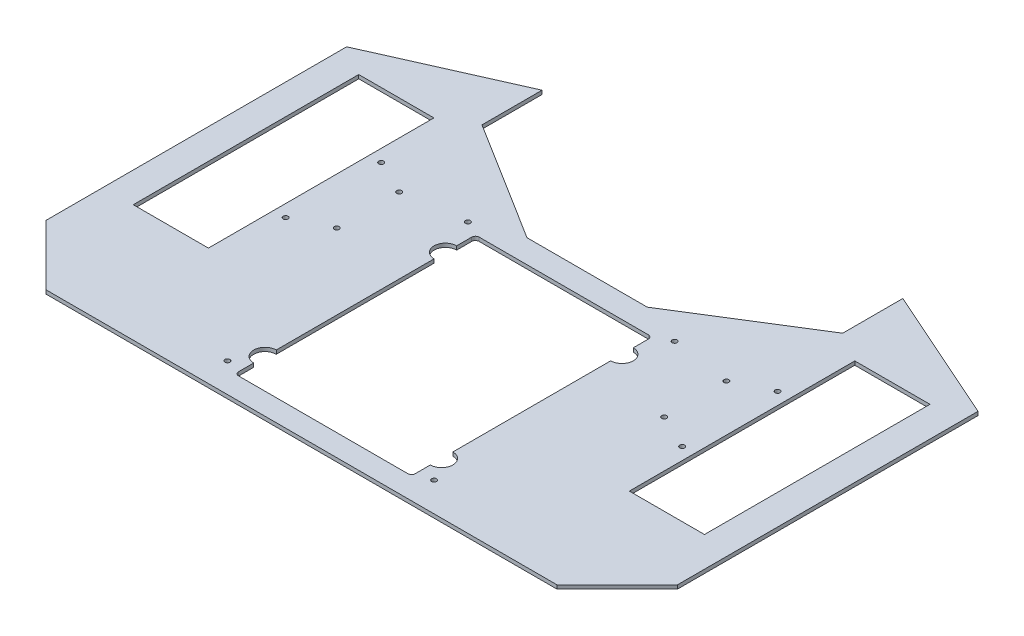
SolidWorks part; units mm, degrees
material "Balsa"
ref_plane "Front Plane" through (0, 0, 0) normal (0, 0, 1) x (1, 0, 0)
ref_plane "Top Plane" through (0, 0, 0) normal (0, 1, 0) x (1, 0, 0)
ref_plane "Right Plane" through (0, 0, 0) normal (1, 0, 0) x (0, 0, -1)
sketch "Sketch1" plane through (0, 0, 0) normal (0, 1, 0) x (1, 0, 0)
  line L17 (265.3132, -148.5502) -> (201.8132, -148.5502) construction
  line L18 (265.3132, -148.5502) -> (265.3132, -339.0502) construction
  line L19 (265.3132, -339.0502) -> (201.8132, -339.0502) construction
  line L20 (201.8132, -148.5502) -> (201.8132, -339.0502) construction
  line L21 (-153.7868, -148.5502) -> (-153.7868, -339.0502) construction
  line L22 (-217.2868, -339.0502) -> (-153.7868, -339.0502) construction
  line L23 (-217.2868, -148.5502) -> (-217.2868, -339.0502) construction
  line L24 (-217.2868, -148.5502) -> (-153.7868, -148.5502) construction
  line L25 (-242.6868, -133.4325) -> (-242.6868, -385.4912) construction
  line L26 (-191.8868, -438.1717) -> (-242.6868, -387.3717) construction
  line L27 (-191.8868, -438.1717) -> (239.9132, -438.1717) construction
  line L28 (239.9132, -438.1717) -> (290.7132, -387.3717) construction
  line L29 (290.7132, -387.3717) -> (290.7132, -133.3717) construction
  line L30 (290.7132, -133.3717) -> (176.4132, -82.5717) construction
  line L31 (176.4132, -82.5717) -> (176.4132, -133.3717) construction
  line L32 (176.4132, -133.3717) -> (74.8132, -196.8717) construction
  line L33 (74.8132, -196.8717) -> (-26.7868, -196.8717) construction
  line L34 (-128.3868, -133.3717) -> (-26.7868, -196.8717) construction
  line L35 (-128.3868, -82.5717) -> (-128.3868, -133.3717) construction
  line L36 (-242.6868, -133.3717) -> (-128.3868, -82.5717) construction
  line L37 (265.3132, -148.5502) -> (201.8132, -148.5502)
  line L38 (265.3132, -148.5502) -> (265.3132, -339.0502)
  line L39 (265.3132, -339.0502) -> (201.8132, -339.0502)
  line L40 (201.8132, -148.5502) -> (201.8132, -339.0502)
  line L41 (-153.7868, -148.5502) -> (-153.7868, -339.0502)
  line L42 (-217.2868, -339.0502) -> (-153.7868, -339.0502)
  line L43 (-217.2868, -148.5502) -> (-217.2868, -339.0502)
  line L44 (-217.2868, -148.5502) -> (-153.7868, -148.5502)
  line L45 (-242.6868, -133.4325) -> (-242.6868, -385.4912)
  line L46 (-191.8868, -438.1717) -> (-242.6868, -387.3717)
  line L47 (-191.8868, -438.1717) -> (239.9132, -438.1717)
  line L48 (239.9132, -438.1717) -> (290.7132, -387.3717)
  line L49 (290.7132, -387.3717) -> (290.7132, -133.3717)
  line L50 (290.7132, -133.3717) -> (176.4132, -82.5717)
  line L51 (176.4132, -82.5717) -> (176.4132, -133.3717)
  line L52 (176.4132, -133.3717) -> (74.8132, -196.8717)
  line L53 (74.8132, -196.8717) -> (-26.7868, -196.8717)
  line L54 (-128.3868, -133.3717) -> (-26.7868, -196.8717)
  line L55 (-128.3868, -82.5717) -> (-128.3868, -133.3717)
  line L56 (-242.6868, -133.3717) -> (-128.3868, -82.5717)
  line L57 (-242.6868, -133.4325) -> (-242.6868, -133.3717)
  line L58 (-242.6868, -385.4912) -> (-242.6868, -387.3717)
extrude "Boss-Extrude1" add sketch "Sketch1" along normal blind 3.175
sketch "Sketch3" plane through (0, 0, 0) normal (0, 1, 0) x (1, 0, 0)
  line L1 (-143.449, -203.465) -> (-143.449, -284.1354) construction
  line L2 (-143.449, -243.8002) -> (24.0132, -243.8002) construction
  line L3 (-191.8868, -438.1717) -> (239.9132, -438.1717) construction
  line L4 (-217.2868, -339.0502) -> (-153.7868, -339.0502) construction
  point P7 (24.0132, -438.1717)
  line B0 (24.0132, -13.4981) -> (24.0132, 49986.5019) construction
  circle B1 centre (-114.2782, -270.1255) radius 2.0828
  circle B2 centre (-143.449, -284.1354) radius 2.0828
  circle B3 centre (-114.2782, -217.4749) radius 2.0828
  circle B4 centre (-143.449, -203.465) radius 2.0828
  circle B5 centre (191.4754, -284.1354) radius 2.0828
  circle B6 centre (162.3046, -270.1255) radius 2.0828
  circle B7 centre (162.3046, -217.4749) radius 2.0828
  circle B8 centre (191.4754, -203.465) radius 2.0828
  dimension "D1" = 95.25
sketch_block_instance "motor_mount_pattern-1"
sketch_block "motor_mount_pattern"
extrude "Cut-Extrude2" cut sketch "Sketch3" along normal through all
sketch "Sketch4" plane through (0, 0, 0) normal (0, 1, 0) x (1, 0, 0)
  line L0 (24.0132, -54.7802) -> (24.0132, -50054.7802) construction
  line L1 (24.0132, -200460.6227) -> (24.0132, 249539.3773) construction
  circle A0 centre (111.3257, -210.2986) radius 2.0828
  circle A1 centre (111.3257, -413.4986) radius 2.0828
  circle A2 centre (-63.2993, -413.4986) radius 2.0828
  circle A3 centre (-63.2993, -210.2986) radius 2.0828
  line B0 (-50.5993, -216.6486) -> (98.6257, -216.6486)
  line B1 (-50.5993, -216.6486) -> (-50.5993, -232.5236)
  line B2 (-50.5993, -419.8486) -> (98.6257, -419.8486)
  line B3 (98.6257, -216.6486) -> (98.6257, -232.5236)
  line B4 (-50.5993, -251.5736) -> (-50.5993, -384.9236)
  line B5 (98.6257, -251.5736) -> (98.6257, -384.9236)
  line B6 (-50.5993, -403.9736) -> (-50.5993, -419.8486)
  line B7 (98.6257, -403.9736) -> (98.6257, -419.8486)
  arc B8 (-50.5993, -232.5236) -> (-50.5993, -251.5736) centre (-50.5993, -242.0486) ccw
  arc B9 (98.6257, -251.5736) -> (98.6257, -232.5236) centre (98.6257, -242.0486) ccw
  arc B10 (-50.5993, -384.9236) -> (-50.5993, -403.9736) centre (-50.5993, -394.4486) ccw
  arc B11 (98.6257, -403.9736) -> (98.6257, -384.9236) centre (98.6257, -394.4486) ccw
  dimension "D5" = 4.1656
  dimension "D1" = 12.7
  dimension "D2" = 6.35
  dimension "D3" = 12.7
  dimension "D4" = 6.35
sketch_block_instance "electronics_cutout-1"
sketch_block "electronics_cutout" parameters "D4"=17.1095, "D6"=25.5924, "D1"=203.2, "D2"=149.225, "D3"=35.6511, "D5"=24.7946
extrude "Cut-Extrude4" cut sketch "Sketch4" along normal through all
fillet "Fillet2" radius 3.175 4 edges at (-50.5993, 1.5875, 419.8486) (98.6257, 1.5875, 419.8486) (98.6257, 1.5875, 216.6486) (-50.5993, 1.5875, 216.6486)
